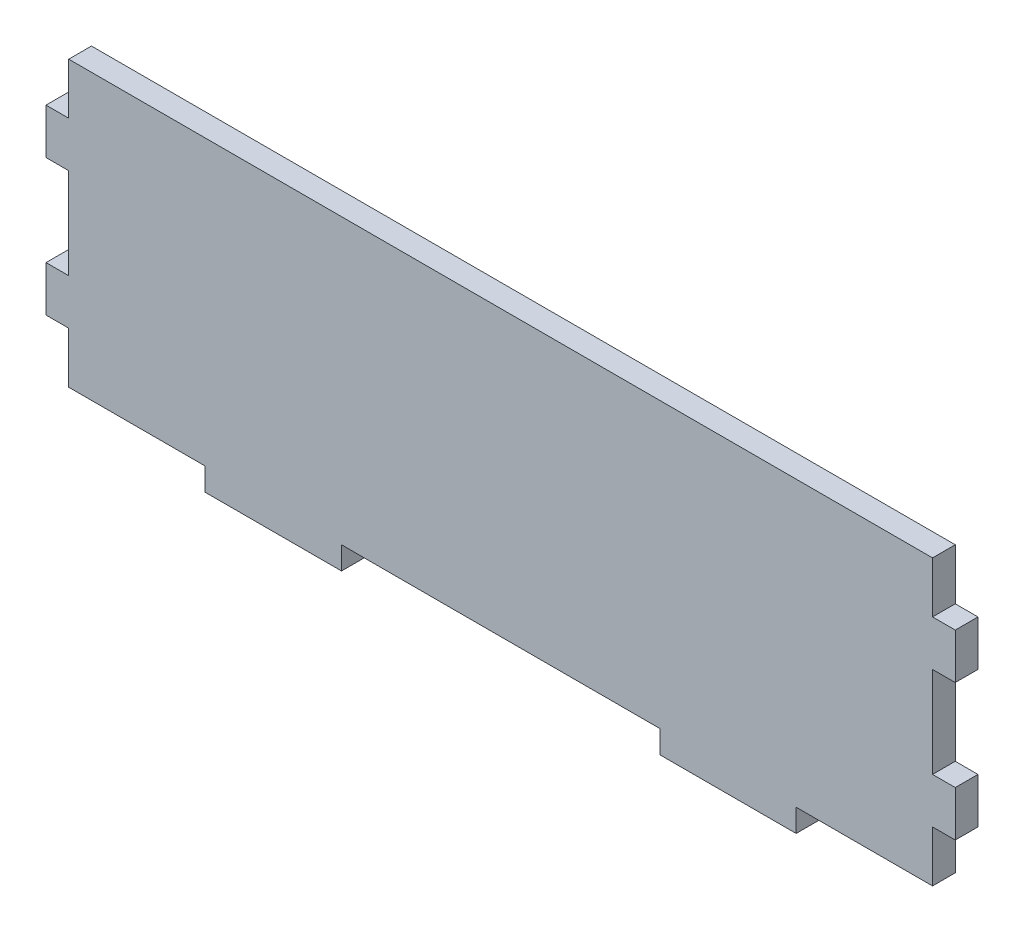
SolidWorks part; units mm, degrees
ref_plane "Front Plane" through (0, 0, 0) normal (0, 0, 1) x (1, 0, 0)
ref_plane "Top Plane" through (0, 0, 0) normal (0, 1, 0) x (1, 0, 0)
ref_plane "Right Plane" through (0, 0, 0) normal (1, 0, 0) x (0, 0, -1)
sketch "Sketch1" plane through (0, 0, 0) normal (0, 0, 1) x (1, 0, 0)
  line L1 (96.52, -63.5) -> (-96.52, -63.5)
  line L2 (96.52, -63.5) -> (96.52, 0)
  line L3 (96.52, 0) -> (-96.52, 0)
  line L4 (-96.52, -63.5) -> (-96.52, 0)
extrude "Boss-Extrude1" add sketch "Sketch1" against normal blind 5.08
sketch "Sketch2" plane through (0, 0, 0) normal (0, 0, 1) x (1, 0, 0)
  line L0 (96.52, -63.5) -> (96.52, 0) construction
  line L1 (101.6, -52.07) -> (96.52, -52.07)
  line L2 (101.6, -52.07) -> (101.6, -41.91)
  line L3 (101.6, -41.91) -> (96.52, -41.91)
  line L4 (96.52, -52.07) -> (96.52, -41.91)
  line L5 (101.6, -41.91) -> (96.52, -41.91) construction
  line L6 (101.6, -21.59) -> (96.52, -21.59) construction
  line L7 (101.6, -11.43) -> (96.52, -11.43)
  line L8 (101.6, -11.43) -> (101.6, -21.59)
  line L9 (101.6, -21.59) -> (96.52, -21.59)
  line L10 (96.52, -11.43) -> (96.52, -21.59)
  line L11 (-96.52, 0) -> (-96.52, -63.5) construction
  line L12 (-96.52, -52.07) -> (-101.6, -52.07)
  line L13 (-96.52, -52.07) -> (-96.52, -41.91)
  line L14 (-96.52, -41.91) -> (-101.6, -41.91)
  line L15 (-101.6, -52.07) -> (-101.6, -41.91)
  line L16 (-96.52, -52.07) -> (-101.6, -52.07) construction
  line L17 (-96.52, -21.59) -> (-101.6, -21.59) construction
  line L18 (-96.52, -21.59) -> (-101.6, -21.59)
  line L19 (-96.52, -21.59) -> (-96.52, -11.43)
  line L20 (-96.52, -11.43) -> (-101.6, -11.43)
  line L21 (-101.6, -21.59) -> (-101.6, -11.43)
extrude "Boss-Extrude2" add sketch "Sketch2" against normal blind 5.08 contours L2 L1 L4 L3 | L8 L7 L10 L9 | L13 L12 L15 L14 | L19 L18 L21 L20
sketch "Sketch3" plane through (0, -63.5, 0) normal (0, -1, 0) x (1, 0, 0)
  line L0 (-96.52, 0) -> (96.52, 0) construction
  line L1 (35.56, 0) -> (66.04, 0)
  line L2 (35.56, 0) -> (35.56, -5.08)
  line L3 (35.56, -5.08) -> (66.04, -5.08)
  line L4 (66.04, 0) -> (66.04, -5.08)
  line L5 (-96.52, -5.08) -> (96.52, -5.08) construction
  line L6 (66.04, 0) -> (66.04, -5.08) construction
  line L7 (-35.56, 0) -> (-35.56, -5.08) construction
  line L8 (-35.56, -5.08) -> (-66.04, -5.08)
  line L9 (-35.56, -5.08) -> (-35.56, 0)
  line L10 (-35.56, 0) -> (-66.04, 0)
  line L11 (-66.04, -5.08) -> (-66.04, 0)
  dimension "D1" = 30.48
  dimension "D2" = 30.48
extrude "Boss-Extrude3" add sketch "Sketch3" along normal blind 5.08
